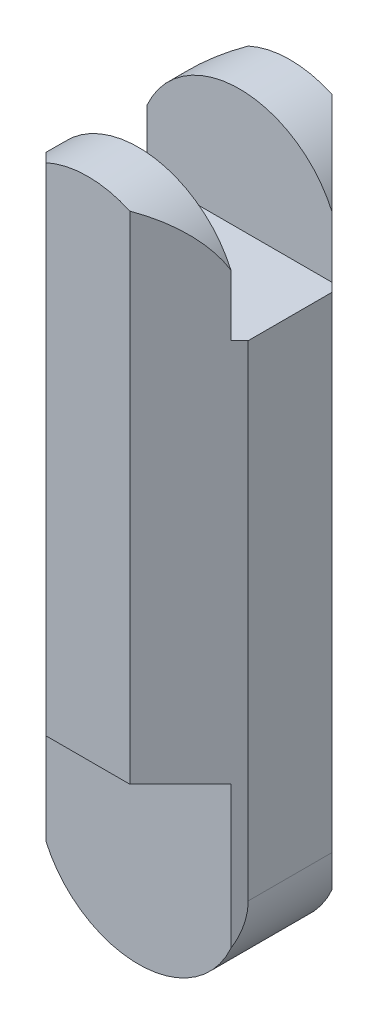
SolidWorks part; units mm, degrees
ref_plane "Front" through (0, 0, 0) normal (0, 0, 1) x (1, 0, 0)
ref_plane "Top" through (0, 0, 0) normal (0, 1, 0) x (1, 0, 0)
ref_plane "Right" through (0, 0, 0) normal (1, 0, 0) x (0, 0, -1)
sketch "草图1" plane through (0, 0, 0) normal (0, 1, 0) x (1, 0, 0)
  line L0 (-12.6518, 0) -> (13.462, 0) construction
  line L1 (0, 11.6722) -> (0, -14.1269) construction
  line L3 (10, 4.1421) -> (4.1421, 10)
  line L4 (4.1421, 10) -> (-4.1421, 10)
  line L5 (-4.1421, 10) -> (-10, 4.1421)
  line L6 (-10, 4.1421) -> (-10, -4.1421)
  line L7 (-10, -4.1421) -> (-4.1421, -10)
  line L8 (-4.1421, -10) -> (4.1421, -10)
  line L9 (4.1421, -10) -> (10, -4.1421)
  line L10 (10, -4.1421) -> (10, 4.1421)
  circle A0 centre (0, 0) radius 10 construction
extrude "凸台-拉伸1" add sketch "草图1" along normal blind 78
sketch "草图2" plane through (0, 0, 10) normal (0, 0, 1) x (1, 0, 0)
  line L0 (0, 0) -> (0, 24) construction
  line L7 (-10, 10) -> (-10, -2.3893)
  line L8 (-10, -2.3893) -> (10, -2.3893)
  line L9 (10, 10) -> (10, -2.3893)
  arc A1 (-10, 10) -> (10, 10) centre (0, 10) ccw
extrude "切除-拉伸1" cut sketch "草图2" against normal blind 66
sketch "草图4" plane through (0, 0, 10) normal (0, 0, 1) x (1, 0, 0)
  line L0 (10, 78) -> (10, 10) construction
  line L2 (-10, 10) -> (-10, 20)
  line L3 (-10, 20) -> (10, 20)
  line L4 (10, 10) -> (10, 20)
  arc A0 (-10, 10) -> (10, 10) centre (0, 10) ccw
extrude "切除-拉伸2" cut sketch "草图4" against normal blind 5
sketch "草图5" plane through (0, 0, -10) normal (0, 0, -1) x (-1, 0, 0)
  line L0 (10, 78) -> (10, 10) construction
  line L2 (-10, 10) -> (-10, 20)
  line L3 (-10, 20) -> (10, 20)
  line L4 (10, 10) -> (10, 20)
  arc A0 (-10, 10) -> (10, 10) centre (0, 10) ccw
extrude "切除-拉伸3" cut sketch "草图5" against normal blind 5
sketch "草图6" plane through (0, 0, 0) normal (0, 0, 1) x (1, 0, 0)
  line L0 (0, 78) -> (0, 0) construction
  line L1 (-4.1421, 78) -> (4.1421, 78) construction
  line L2 (10, 78) -> (10, 10) construction
  line L3 (-10, 78) -> (10, 78)
  line L4 (-10, 78) -> (-10, 58)
  line L5 (-10, 58) -> (10, 58)
  line L6 (10, 78) -> (10, 58)
  dimension "D1" = 20
extrude "切除-拉伸4" cut sketch "草图6" against normal mid plane 10
sketch "草图7" plane through (0, 0, 10) normal (0, 0, 1) x (1, 0, 0)
  line L0 (0, 78) -> (0, 0) construction
  line L1 (-4.1421, 78) -> (4.1421, 78) construction
  line L4 (-10, 60) -> (-10, 79.1079)
  line L5 (-10, 79.1079) -> (10, 79.1079)
  line L6 (10, 60) -> (10, 79.1079)
  arc A0 (10, 60) -> (-10, 60) centre (0, 60) ccw
extrude "切除-拉伸5" cut sketch "草图7" against normal blind 30
